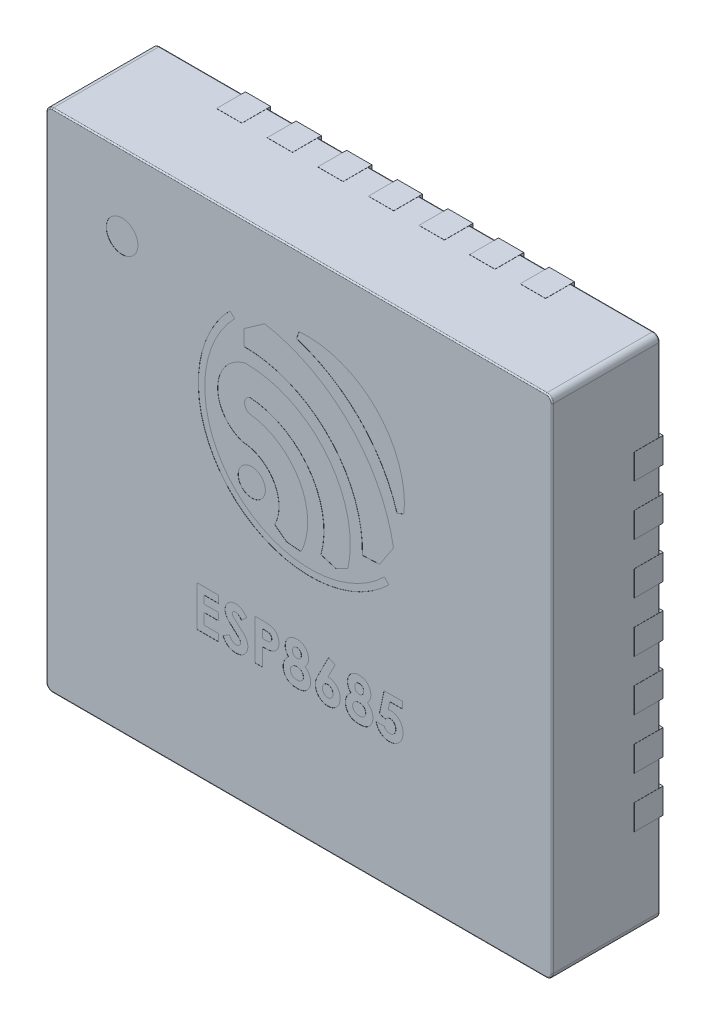
SolidWorks part; units mm, degrees
other "ESP8685-SoC" parameters "D1"=142.8057, "D2"=5.389, "D3"=0.5075, "D4"=0.5075, "D5"=0.3678, "D6"=0.3296, "D7"=0.2637, "D8"=0.9806, "D10"=0.5, "D11"=0.25, "D9"=0.4
ref_plane "Front Plane" through (0, 0, 0) normal (0, 0, 1) x (1, 0, 0)
ref_plane "Top Plane" through (0, 0, 0) normal (0, 1, 0) x (1, 0, 0)
ref_plane "Right Plane" through (0, 0, 0) normal (1, 0, 0) x (0, 0, -1)
sketch "Sketch1" plane through (0, 0, 0) normal (0, 1, 0) x (1, 0, 0)
  line L1 (-2, -2) -> (2, -2)
  line L2 (-2, -2) -> (-2, 2)
  line L3 (-2, 2) -> (2, 2)
  line L4 (2, -2) -> (2, 2)
  line L5 (-2, -2) -> (2, 2) construction
  line L6 (-2, 2) -> (2, -2) construction
  point P0 (0, 0)
  dimension "D1" = 4
  dimension "D2" = 4
extrude "Boss-Extrude1" add sketch "Sketch1" along normal blind 0.85
fillet "Fillet1" radius 0.05 4 edges at (2, 0.425, -2) (2, 0.425, 2) (-2, 0.425, 2) (-2, 0.425, -2)
fillet "Fillet2" radius 0.01 16 edges at (1.9854, 0.85, 1.9854) (0, 0.85, 2) (-1.9854, 0.85, 1.9854) (-2, 0.85, 0) (-1.9854, 0.85, -1.9854) (0, 0.85, -2) (1.9854, 0.85, -1.9854) (2, 0.85, 0) (2, 0, 0) (1.9854, 0, -1.9854) (0, 0, -2) (1.9854, 0, 1.9854) (0, 0, 2) (-1.9854, 0, 1.9854) (-2, 0, 0) (-1.9854, 0, -1.9854)
sketch "Sketch2" plane through (0, 0, 0) normal (0, -1, 0) x (1, 0, 0)
  line L0 (1.05, 1.35) -> (1.35, 1.05)
  line L1 (-1.3, -1.35) -> (1.3, -1.35)
  line L2 (-1.35, -1.3) -> (-1.35, 1.3)
  line L3 (-1.3, 1.35) -> (1.05, 1.35)
  line L4 (1.35, -1.3) -> (1.35, 1.05)
  line L5 (-1.3354, -1.3354) -> (1.35, 1.35) construction
  line L6 (-1.3354, 1.3354) -> (1.3354, -1.3354) construction
  line L7 (1.05, 1.35) -> (1.35, 1.35) construction
  line L8 (1.35, 1.05) -> (1.35, 1.35) construction
  line L9 (-1.35, 1.35) -> (-1.3, 1.35) construction
  line L10 (-1.35, 1.35) -> (-1.3354, 1.3354) construction
  line L11 (-1.35, 1.3) -> (-1.35, 1.35) construction
  line L12 (-1.35, -1.35) -> (-1.35, -1.3) construction
  line L13 (-1.35, -1.35) -> (-1.3354, -1.3354) construction
  line L14 (-1.35, -1.35) -> (-1.3, -1.35) construction
  line L15 (1.35, -1.35) -> (1.35, -1.3) construction
  line L16 (1.3354, -1.3354) -> (1.35, -1.35) construction
  line L17 (1.3, -1.35) -> (1.35, -1.35) construction
  line L18 (0, -1000) -> (0, 49000) construction
  line L23 (-0.1, 2.001) -> (0.1, 2.001)
  line L24 (-0.1, 2.001) -> (-0.1, 1.651)
  line L25 (-0.1, 1.651) -> (0.1, 1.651)
  line L26 (0.1, 2.001) -> (0.1, 1.651)
  line L27 (-0.1, 2.001) -> (0.1, 1.651) construction
  line L28 (-0.1, 1.651) -> (0.1, 2.001) construction
  line L34 (-0.5, 2.001) -> (-0.5, 1.651)
  line L35 (-0.5, 2.001) -> (-0.3, 2.001)
  line L40 (-0.3, 2.001) -> (-0.3, 1.651)
  line L41 (-0.5, 1.651) -> (-0.3, 1.651)
  line L46 (-0.9, 2.001) -> (-0.9, 1.651)
  line L47 (-0.9, 2.001) -> (-0.7, 2.001)
  line L48 (-0.7, 2.001) -> (-0.7, 1.651)
  line L49 (-0.9, 1.651) -> (-0.7, 1.651)
  line L66 (-1.3, 2.001) -> (-1.3, 1.651)
  line L162 (-1000, 0) -> (49000, 0) construction
  line L163 (-2, 2) -> (2, 2) construction
  line L164 (-1.3, 2.001) -> (-1.1, 2.001)
  line L165 (-1.1, 2.001) -> (-1.1, 1.651)
  line L166 (-1.3, 1.651) -> (-1.1, 1.651)
  line L167 (-0.1, 2.001) -> (-0.5, 2.001) construction
  line L168 (1.3, 1.651) -> (1.1, 1.651)
  line L169 (1.1, 2.001) -> (1.1, 1.651)
  line L170 (1.3, 2.001) -> (1.1, 2.001)
  line L171 (1.3, 2.001) -> (1.3, 1.651)
  line L172 (0.9, 1.651) -> (0.7, 1.651)
  line L189 (0.7, 2.001) -> (0.7, 1.651)
  line L190 (0.9, 2.001) -> (0.7, 2.001)
  line L191 (0.9, 2.001) -> (0.9, 1.651)
  line L192 (0.5, 1.651) -> (0.3, 1.651)
  line L193 (0.3, 2.001) -> (0.3, 1.651)
  line L194 (0.5, 2.001) -> (0.3, 2.001)
  line L195 (0.5, 2.001) -> (0.5, 1.651)
  line L196 (-0.1, -2.001) -> (-0.5, -2.001) construction
  line L197 (-0.1, -1.651) -> (0.1, -2.001) construction
  line L198 (-0.1, -2.001) -> (0.1, -1.651) construction
  line L199 (0.5, -2.001) -> (0.5, -1.651)
  line L200 (0.5, -2.001) -> (0.3, -2.001)
  line L201 (0.3, -2.001) -> (0.3, -1.651)
  line L202 (0.5, -1.651) -> (0.3, -1.651)
  line L203 (0.9, -2.001) -> (0.9, -1.651)
  line L204 (0.9, -2.001) -> (0.7, -2.001)
  line L205 (0.7, -2.001) -> (0.7, -1.651)
  line L206 (0.9, -1.651) -> (0.7, -1.651)
  line L239 (1.3, -2.001) -> (1.3, -1.651)
  line L240 (1.3, -2.001) -> (1.1, -2.001)
  line L241 (1.1, -2.001) -> (1.1, -1.651)
  line L242 (1.3, -1.651) -> (1.1, -1.651)
  line L243 (-1.3, -1.651) -> (-1.1, -1.651)
  line L244 (-1.1, -2.001) -> (-1.1, -1.651)
  line L245 (-1.3, -2.001) -> (-1.1, -2.001)
  line L246 (-1.3, -2.001) -> (-1.3, -1.651)
  line L247 (-0.9, -1.651) -> (-0.7, -1.651)
  line L248 (-0.7, -2.001) -> (-0.7, -1.651)
  line L249 (-0.9, -2.001) -> (-0.7, -2.001)
  line L250 (-0.9, -2.001) -> (-0.9, -1.651)
  line L251 (-0.5, -1.651) -> (-0.3, -1.651)
  line L252 (-0.3, -2.001) -> (-0.3, -1.651)
  line L253 (-0.5, -2.001) -> (-0.3, -2.001)
  line L254 (-0.5, -2.001) -> (-0.5, -1.651)
  line L255 (0.1, -2.001) -> (0.1, -1.651)
  line L256 (-0.1, -1.651) -> (0.1, -1.651)
  line L289 (-0.1, -2.001) -> (-0.1, -1.651)
  line L290 (-0.1, -2.001) -> (0.1, -2.001)
  line L291 (2.001, 0.1) -> (1.651, -0.1) construction
  line L292 (1.651, 0.1) -> (2.001, -0.1) construction
  line L293 (2.001, 0.1) -> (2.001, 0.5) construction
  line L294 (2.001, 0.1) -> (2.001, -0.1)
  line L295 (2.001, 0.1) -> (1.651, 0.1)
  line L296 (1.651, 0.1) -> (1.651, -0.1)
  line L297 (2.001, -0.1) -> (1.651, -0.1)
  line L298 (2.001, 0.5) -> (1.651, 0.5)
  line L299 (2.001, 0.5) -> (2.001, 0.3)
  line L300 (2.001, 0.3) -> (1.651, 0.3)
  line L301 (1.651, 0.5) -> (1.651, 0.3)
  line L302 (2.001, 0.9) -> (1.651, 0.9)
  line L303 (2.001, 0.9) -> (2.001, 0.7)
  line L304 (2.001, 0.7) -> (1.651, 0.7)
  line L305 (1.651, 0.9) -> (1.651, 0.7)
  line L306 (2.001, 1.3) -> (1.651, 1.3)
  line L339 (2.001, 1.3) -> (2.001, 1.1)
  line L340 (2.001, 1.1) -> (1.651, 1.1)
  line L341 (1.651, 1.3) -> (1.651, 1.1)
  line L342 (1.651, -1.3) -> (1.651, -1.1)
  line L343 (2.001, -1.1) -> (1.651, -1.1)
  line L344 (2.001, -1.3) -> (2.001, -1.1)
  line L345 (2.001, -1.3) -> (1.651, -1.3)
  line L346 (1.651, -0.9) -> (1.651, -0.7)
  line L347 (2.001, -0.7) -> (1.651, -0.7)
  line L348 (2.001, -0.9) -> (2.001, -0.7)
  line L349 (2.001, -0.9) -> (1.651, -0.9)
  line L350 (1.651, -0.5) -> (1.651, -0.3)
  line L351 (2.001, -0.3) -> (1.651, -0.3)
  line L352 (2.001, -0.5) -> (2.001, -0.3)
  line L353 (2.001, -0.5) -> (1.651, -0.5)
  line L354 (-2.001, 0.1) -> (-2.001, 0.5) construction
  line L355 (-1.651, 0.1) -> (-2.001, -0.1) construction
  line L356 (-2.001, 0.1) -> (-1.651, -0.1) construction
  line L357 (-2.001, -0.5) -> (-1.651, -0.5)
  line L358 (-2.001, -0.5) -> (-2.001, -0.3)
  line L359 (-2.001, -0.3) -> (-1.651, -0.3)
  line L360 (-1.651, -0.5) -> (-1.651, -0.3)
  line L361 (-2.001, -0.9) -> (-1.651, -0.9)
  line L362 (-2.001, -0.9) -> (-2.001, -0.7)
  line L363 (-2.001, -0.7) -> (-1.651, -0.7)
  line L364 (-1.651, -0.9) -> (-1.651, -0.7)
  line L365 (-2.001, -1.3) -> (-1.651, -1.3)
  line L366 (-2.001, -1.3) -> (-2.001, -1.1)
  line L367 (-2.001, -1.1) -> (-1.651, -1.1)
  line L368 (-1.651, -1.3) -> (-1.651, -1.1)
  line L369 (-1.651, 1.3) -> (-1.651, 1.1)
  line L370 (-2.001, 1.1) -> (-1.651, 1.1)
  line L371 (-2.001, 1.3) -> (-2.001, 1.1)
  line L372 (-2.001, 1.3) -> (-1.651, 1.3)
  line L373 (-1.651, 0.9) -> (-1.651, 0.7)
  line L374 (-2.001, 0.7) -> (-1.651, 0.7)
  line L375 (-2.001, 0.9) -> (-2.001, 0.7)
  line L376 (-2.001, 0.9) -> (-1.651, 0.9)
  line L377 (-1.651, 0.5) -> (-1.651, 0.3)
  line L378 (-2.001, 0.3) -> (-1.651, 0.3)
  line L379 (-2.001, 0.5) -> (-2.001, 0.3)
  line L380 (-2.001, 0.5) -> (-1.651, 0.5)
  line L381 (-2.001, -0.1) -> (-1.651, -0.1)
  line L382 (-1.651, 0.1) -> (-1.651, -0.1)
  line L383 (-2.001, 0.1) -> (-1.651, 0.1)
  line L384 (-2.001, 0.1) -> (-2.001, -0.1)
  arc A0 (-1.3, 1.35) -> (-1.35, 1.3) centre (-1.3, 1.3) ccw
  arc A1 (-1.35, -1.3) -> (-1.3, -1.35) centre (-1.3, -1.3) ccw
  arc A2 (1.3, -1.35) -> (1.35, -1.3) centre (1.3, -1.3) ccw
  point P0 (0, 0)
  point P12 (0, 1.826)
  point P85 (0, -1.826)
  point P114 (1.826, 0)
  point P143 (-1.826, 0)
  dimension "D5" = 0.1
  dimension "D1" = 2.7
  dimension "D2" = 2.7
  dimension "D4" = 45
  dimension "D6" = 0.35
  dimension "D7" = 0.2
  dimension "D11" = 0.001
  dimension "D3" = 0.3
  dimension "D8" = 4
extrude "Boss-Extrude2" add sketch "Sketch2" along normal blind 0.025 and the other way blind 0.203
sketch "Sketch3" plane through (0, 0.85, 0) normal (0, 1, 0) x (1, 0, 0)
  line L7 (-2, 0.995) -> (2, 0.995) construction
  line L8 (-2, 2) -> (-2, -2) construction
  line L9 (-0.7733, -0.5895) -> (-0.8285, -0.613)
  line L11 (2, 1.95) -> (2, -1.95) construction
  line L12 (1.95, -2) -> (-1.95, -2) construction
  line L13 (0.0008, -1.4466) -> (0.0218, -1.3879)
  line L14 (-0.499, -0.1656) -> (-0.6351, -0.1714)
  line L15 (-0.6351, -0.1714) -> (-0.7451, -0.3394)
  line L16 (0.2724, -1.3646) -> (0.4376, -1.2487)
  line L17 (0.4376, -1.2487) -> (0.4376, -1.127)
  line L18 (0.5099, -1.2811) -> (0.5484, -1.3152)
  line L19 (-0.7076, -0.0671) -> (-0.6734, -0.1054)
  line L20 (0.1943, -0.0295) -> (0.0996, 0.0421)
  line L21 (0.0996, 0.0421) -> (-0.0141, 0.0521)
  line L22 (-0.1711, -0.0059) -> (-0.2912, 0.0299)
  line L23 (-0.2912, 0.0299) -> (-0.3849, -0.017)
  line L24 (0, 0) -> (0, 1.99) construction
  line L25 (1.95, 1.99) -> (-1.95, 1.99) construction
  arc A10 (-0.7733, -0.5895) -> (0.0218, -1.3879) centre (0.375, -0.2411) ccw
  circle A12 centre (1.4, -1.4) radius 0.125
  arc A13 (-0.7451, -0.3394) -> (0.2724, -1.3646) centre (0.4965, -0.1247) ccw
  arc A14 (0.4238, -1.0184) -> (0.4474, -0.4688) centre (0.3594, -0.7404) ccw
  arc A15 (0.5484, -1.3152) -> (-0.7076, -0.0671) centre (-0.0877, -0.6993) ccw
  circle A16 centre (0.375, -0.2278) radius 0.1075
  arc A17 (-0.1711, -0.0059) -> (0.3893, -0.8012) centre (0.4289, -0.1782) ccw
  arc A18 (0.1943, -0.0295) -> (0.4474, -0.4688) centre (0.4602, -0.1689) ccw
  arc A19 (-0.0141, 0.0521) -> (0.3914, -0.6883) centre (0.4487, -0.1757) ccw
  arc A20 (-0.3849, -0.017) -> (0.4238, -1.0184) centre (0.4241, -0.191) ccw
  arc A21 (0.5099, -1.2811) -> (-0.6734, -0.1054) centre (-0.0877, -0.6993) ccw
  arc A22 (-0.499, -0.1656) -> (0.4376, -1.127) centre (0.4366, -0.1911) ccw
  arc A23 (0.3914, -0.6883) -> (0.3893, -0.8012) centre (0.3725, -0.7444) cw
  arc A24 (-0.8285, -0.613) -> (0.0008, -1.4466) centre (-0.0629, -0.6806) ccw
  text T0 "ESP8685" font "Century Gothic" height 0.32
  point P0 (0, 0.995)
  point P52 (0, 0)
  dimension "D2" = 0.25
  dimension "D3" = 0.6
  dimension "D4" = 0.6
extrude "Cut-Extrude1" cut sketch "Sketch3" against normal blind 0.001
move or copy body "Body-Move/Copy1" bodies to move or copy 131 copy no rotation origin (0, 0, 0) rotation axis (0, 0.7071, 0.7071) rotation angle 180
move or copy body "Body-Move/Copy2" bodies to move or copy 132 copy no translate (0, 0, 0.025)
equation "\"D1@Sketch1\"=\"D2@Sketch1\""
equation "\"D4@Sketch3\"=\"D3@Sketch3\""
equation "\"D1@Sketch2\"=\"D2@Sketch2\""
